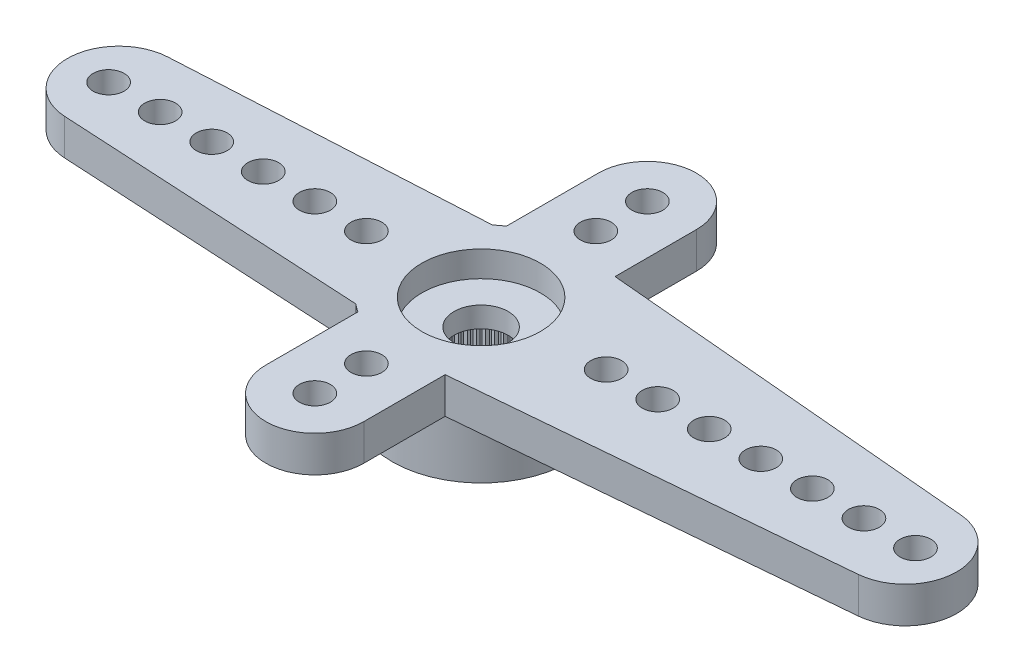
SolidWorks part; units mm, degrees
material "PVC Rígido"
ref_plane "Plano frontal" through (0, 0, 0) normal (0, 0, 1) x (1, 0, 0)
ref_plane "Plano superior" through (0, 0, 0) normal (0, 1, 0) x (1, 0, 0)
ref_plane "Plano direito" through (0, 0, 0) normal (1, 0, 0) x (0, 0, -1)
sketch "Esboço1" plane through (0, 0, 0) normal (0, 1, 0) x (1, 0, 0)
  line L0 (0, 0) -> (-14.05, 0) construction
  line L1 (-14.1591, 1.997) -> (-2.2091, 2.65)
  line L2 (-2.2091, -2.65) -> (-14.1591, -1.997)
  arc A0 (-2.2091, -2.65) -> (-2.2091, 2.65) centre (0, 0) ccw
  arc A1 (-14.1591, 1.997) -> (-14.1591, -1.997) centre (-14.05, 0) ccw
  dimension "D1" = 6.9
  dimension "D2" = 4
  dimension "D3" = 19.5
  dimension "D4" = 5.3
extrude "Ressalto-extrusão1" add sketch "Esboço1" against normal blind 1.4
sketch "Esboço2" plane through (0, -1.4, 0) normal (0, -1, 0) x (1, 0, 0)
  arc A0 (-2.2091, -2.65) -> (-2.2091, 2.65) centre (0, 0) ccw construction
  circle A1 centre (0, 0) radius 3.45
extrude "Ressalto-extrusão2" add sketch "Esboço2" along normal offset from surface (2.4 mm away) 3.8 up to face at (-7.242, 0, 0)
hole_wizard "Furo1" positions "Esboço9" profile "Esboço10" legacy end condition through all
sketch "Esboço9" plane through (0, 0, 0) normal (0, 1, 0) x (1, 0, 0)
  line L1 (-14.45, 0) -> (0, 0) construction
  arc A2 (-14.1591, 1.997) -> (-14.1591, -1.997) centre (-14.05, 0) ccw construction
  point P0 (-14.45, 0)
  point P19 (-16.05, 0)
  dimension "D1" = 1.6
sketch "Esboço10" plane through (-14.45, 0, 0) normal (1, 0, 0) x (0, 0, 1)
  line L0 (0, 0) -> (0, 3.8)
  line L1 (0, 3.8) -> (0.6, 3.8)
  line L2 (0.6, 3.8) -> (0.6, 0)
  line L3 (0.6, 0) -> (0, 0)
  line L4 (0, 110) -> (0, -10) construction
  dimension "Diameter" = 1.2
  dimension "Depth" = 3.8
pattern_linear "Padrão linear1" count 6 spacing 2 along (1, 0, 0) of "Furo1"
sketch "Esboço12" plane through (0, 0, 0) normal (0, 1, 0) x (1, 0, 0)
  line L0 (0.3041, 3.4366) -> (16.6263, 1.9922)
  line L1 (16.6263, -1.9922) -> (0.3041, -3.4366)
  arc A0 (-2.2091, -2.65) -> (-2.2091, 2.65) centre (0, 0) ccw construction
  arc A1 (0.3041, -3.4366) -> (0.3041, 3.4366) centre (0, 0) ccw
  arc A2 (16.6263, 1.9922) -> (16.6263, -1.9922) centre (16.45, 0) cw
  arc A3 (-14.1591, 1.997) -> (-14.1591, -1.997) centre (-14.05, 0) ccw construction
  dimension "D1" = 2
  dimension "D2" = 34.5
extrude "Ressalto-extrusão3" add sketch "Esboço12" against normal up to surface (1.4 mm away) up to face at (-12.45, -1.4, 0.6)
hole_wizard "Furo2" positions "Esboço13" profile "Esboço14" legacy end condition through all
sketch "Esboço13" plane through (0, 0, 0) normal (0, 1, 0) x (1, 0, 0)
  line L0 (0, 0) -> (16.85, 0) construction
  arc A0 (16.6263, -1.9922) -> (16.6263, 1.9922) centre (16.45, 0) ccw construction
  point P0 (16.85, 0)
  point P6 (18.45, 0)
  dimension "D1" = 1.6
sketch "Esboço14" plane through (16.85, 0, 0) normal (1, 0, 0) x (0, 0, 1)
  line L0 (0, 0) -> (0, 3.8)
  line L1 (0, 3.8) -> (0.6, 3.8)
  line L2 (0.6, 3.8) -> (0.6, 0)
  line L3 (0.6, 0) -> (0, 0)
  line L4 (0, 110) -> (0, -10) construction
  dimension "Diameter" = 1.2
  dimension "Depth" = 3.8
pattern_linear "Padrão linear2" count 7 spacing 2 along (-1, 0, 0) of "Furo2"
sketch "Esboço16" plane through (0, 0, 0) normal (0, 1, 0) x (1, 0, 0)
  line L0 (0, -6.45) -> (0, 6.45) construction
  line L1 (-1.9, -6.45) -> (-1.9, 6.45)
  line L2 (1.9, -6.45) -> (1.9, 6.45)
  arc A0 (-1.9, -6.45) -> (1.9, -6.45) centre (0, -6.45) ccw
  arc A1 (1.9, 6.45) -> (-1.9, 6.45) centre (0, 6.45) ccw
  point P2 (0, 0)
  dimension "D2" = 16.7
  dimension "D1" = 3.8
extrude "Ressalto-extrusão4" add sketch "Esboço16" against normal up to surface (1.4 mm away) up to face at (14.85, -1.4, 0.6)
hole_wizard "Furo3" positions "Esboço17" profile "Esboço18" legacy end condition through all
sketch "Esboço17" plane through (0, 0, 0) normal (0, 1, 0) x (1, 0, 0)
  point P0 (0, -6.45)
sketch "Esboço18" plane through (0, 0, 6.45) normal (1, 0, 0) x (0, 0, 1)
  line L0 (0, 0) -> (0, 3.8)
  line L1 (0, 3.8) -> (0.6, 3.8)
  line L2 (0.6, 3.8) -> (0.6, 0)
  line L3 (0.6, 0) -> (0, 0)
  line L4 (0, 110) -> (0, -10) construction
  dimension "Diameter" = 1.2
  dimension "Depth" = 3.8
pattern_linear "Padrão linear3" count 2 spacing 2 along (0, 0, -1) of "Furo3"
pattern_circular "PadrãoCircular1" count 2 over 360 about axis through (0, 0, 0) along (0, 1, 0) of "Padrão linear3", "Furo3"
hole_wizard "Furo4" positions "Esboço3" profile "Esboço4" legacy
sketch "Esboço3" plane through (0, -3.8, 0) normal (0, -1, 0) x (-1, 0, 0)
  point P0 (0, 0)
sketch "Esboço4" plane through (0, -3.8, 0) normal (1, 0, 0) x (0, 0, -1)
  line L0 (0, 0) -> (0, 2)
  line L1 (0, 2) -> (2.475, 2)
  line L2 (2.475, 2) -> (2.475, 0)
  line L3 (2.475, 0) -> (0, 0)
  line L4 (0, 110) -> (0, -10) construction
  dimension "Diameter" = 4.95
  dimension "Depth" = 2
hole_wizard "Furo5" positions "Esboço5" profile "Esboço6" legacy
sketch "Esboço5" plane through (0, 0, 0) normal (0, 1, 0) x (1, 0, 0)
  point P0 (0, 0)
sketch "Esboço6" plane through (0, 0, 0) normal (1, 0, 0) x (0, 0, 1)
  line L0 (0, 0) -> (0, 1)
  line L1 (0, 1) -> (2.3, 1)
  line L2 (2.3, 1) -> (2.3, 0)
  line L3 (2.3, 0) -> (0, 0)
  line L4 (0, 110) -> (0, -10) construction
  dimension "Diameter" = 4.6
  dimension "Depth" = 1
hole_wizard "Furo6" positions "Esboço7" profile "Esboço8" legacy end condition through all
sketch "Esboço7" plane through (0, 0, 0) normal (0, 1, 0) x (1, 0, 0)
  point P0 (0, 0)
sketch "Esboço8" plane through (0, 0, 0) normal (1, 0, 0) x (0, 0, 1)
  line L0 (0, 0) -> (0, 3.8)
  line L1 (0, 3.8) -> (1.05, 3.8)
  line L2 (1.05, 3.8) -> (1.05, 0)
  line L3 (1.05, 0) -> (0, 0)
  line L4 (0, 110) -> (0, -10) construction
  dimension "Diameter" = 2.1
  dimension "Depth" = 3.8
sketch "Esboço11" plane through (0, -3.8, 0) normal (0, -1, 0) x (1, 0, 0)
  line L0 (-0.0981, 2.4731) -> (0, 2.375)
  line L1 (0, 2.375) -> (0.0981, 2.4731)
  line L2 (0, 0) -> (0, 2.475) construction
  circle A0 centre (0, 0) radius 2.375 construction
  circle A1 centre (0, 0) radius 2.475
  arc A2 (0.0981, 2.4731) -> (-0.0981, 2.4731) centre (0, 0) ccw
  dimension "D3" = 4.75
  dimension "D2" = 0.1
  dimension "D1" = 0
extrude "Ressalto-extrusão5" add sketch "Esboço11" against normal up to surface (2 mm away) up to face at (0, -1.8, 1.05)
pattern_circular "PadrãoCircular2" count 60 over 360 about axis through (0, 0, 0) along (0, 1, 0) of "Ressalto-extrusão5"
sketch "Sketch1" plane through (0, 0, 0) normal (0, 1, 0) x (1, 0, 0)
  line L8 (-1.9, 6.45) -> (-1.9, 2.8797)
  line L9 (-2.2091, 2.65) -> (-14.1591, 1.997)
  line L10 (-14.1591, -1.997) -> (-2.2091, -2.65)
  line L11 (-1.9, -2.8797) -> (-1.9, -6.45)
  line L12 (1.9, -6.45) -> (1.9, -3.2953)
  line L13 (1.9, -3.2953) -> (16.6263, -1.9922)
  line L14 (16.6263, 1.9922) -> (1.9, 3.2953)
  line L15 (1.9, 3.2953) -> (1.9, 6.45)
  line L16 (-1.9, 6.45) -> (-1.9, 2.8797)
  line L17 (-2.2091, 2.65) -> (-14.1591, 1.997)
  line L18 (-14.1591, -1.997) -> (-2.2091, -2.65)
  line L19 (-1.9, -2.8797) -> (-1.9, -6.45)
  line L20 (1.9, -6.45) -> (1.9, -3.2953)
  line L21 (1.9, -3.2953) -> (16.6263, -1.9922)
  line L22 (16.6263, 1.9922) -> (1.9, 3.2953)
  line L23 (1.9, 3.2953) -> (1.9, 6.45)
  arc A6 (-1.9, 2.8797) -> (-2.2091, 2.65) centre (0, 0) ccw
  arc A7 (-14.1591, 1.997) -> (-14.1591, -1.997) centre (-14.05, 0) ccw
  arc A8 (-2.2091, -2.65) -> (-1.9, -2.8797) centre (0, 0) ccw
  arc A9 (-1.9, -6.45) -> (1.9, -6.45) centre (0, -6.45) ccw
  arc A10 (16.6263, -1.9922) -> (16.6263, 1.9922) centre (16.45, 0) ccw
  arc A11 (1.9, 6.45) -> (-1.9, 6.45) centre (0, 6.45) ccw
  arc A12 (-1.9, 2.8797) -> (-2.2091, 2.65) centre (0, 0) ccw
  arc A13 (-14.1591, 1.997) -> (-14.1591, -1.997) centre (-14.05, 0) ccw
  arc A14 (-2.2091, -2.65) -> (-1.9, -2.8797) centre (0, 0) ccw
  arc A15 (-1.9, -6.45) -> (1.9, -6.45) centre (0, -6.45) ccw
  arc A16 (16.6263, -1.9922) -> (16.6263, 1.9922) centre (16.45, 0) ccw
  arc A17 (1.9, 6.45) -> (-1.9, 6.45) centre (0, 6.45) ccw
  dimension "D1" = 0
